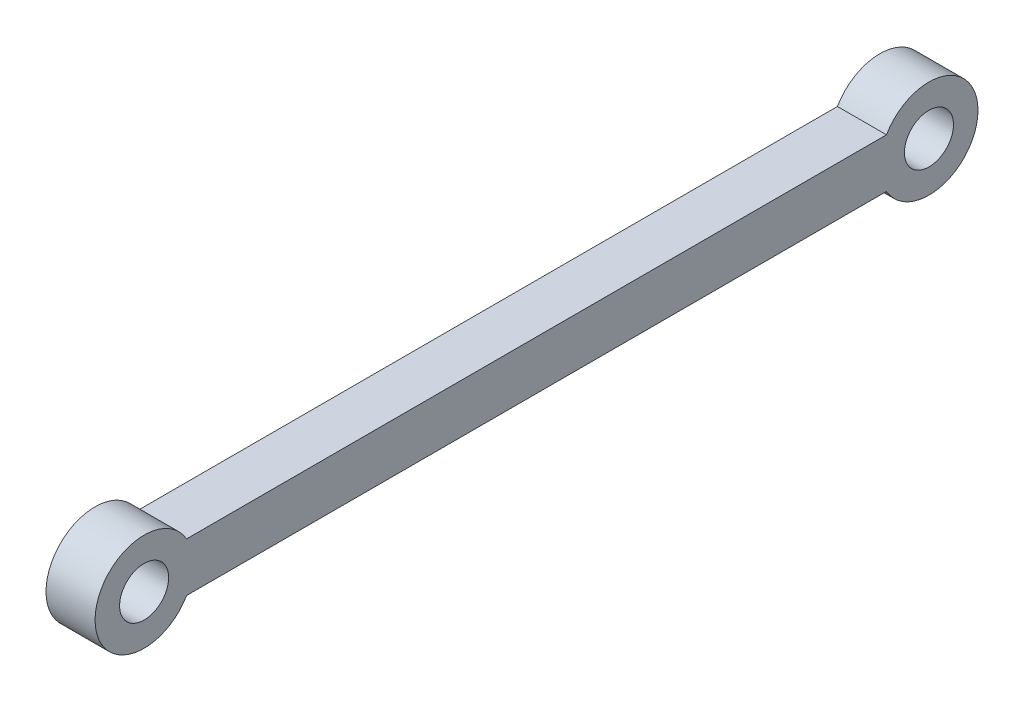
SolidWorks part; units mm, degrees
ref_plane "정면" through (0, 0, 0) normal (0, 0, 1) x (1, 0, 0)
ref_plane "윗면" through (0, 0, 0) normal (0, 1, 0) x (1, 0, 0)
ref_plane "우측면" through (0, 0, 0) normal (1, 0, 0) x (0, 0, -1)
sketch "스케치1" plane through (0, 0, 0) normal (1, 0, 0) x (0, 0, -1)
  line L0 (-20, 0) -> (20, 0) construction
  line L1 (-17.8349, 1.25) -> (17.8349, 1.25)
  line L3 (-17.8349, -1.25) -> (17.8349, -1.25)
  line L5 (0, 1.25) -> (0, -1.25) construction
  arc A0 (-17.8349, 1.25) -> (-17.8349, -1.25) centre (-20, 0) ccw
  circle A1 centre (-20, 0) radius 1.25
  arc A2 (17.8349, -1.25) -> (17.8349, 1.25) centre (20, 0) ccw
  circle A3 centre (20, 0) radius 1.25
  dimension "D3" = 5
  dimension "D4" = 5
  dimension "D1" = 2.5
  dimension "D2" = 40
extrude "보스-돌출1" add sketch "스케치1" along normal blind 2.5
equation "\"link11\" = 80"
equation "\"link12\" = 40"
equation "\"link21\"= 60"
equation "\"link22\"= 40"
equation "\"link31\"= 50"
equation "\"link32\"= 40"
equation "\"link41\"= 40"
equation "\"link42\"= 40"
equation "\"D2@스케치1\"=\"link12\""
